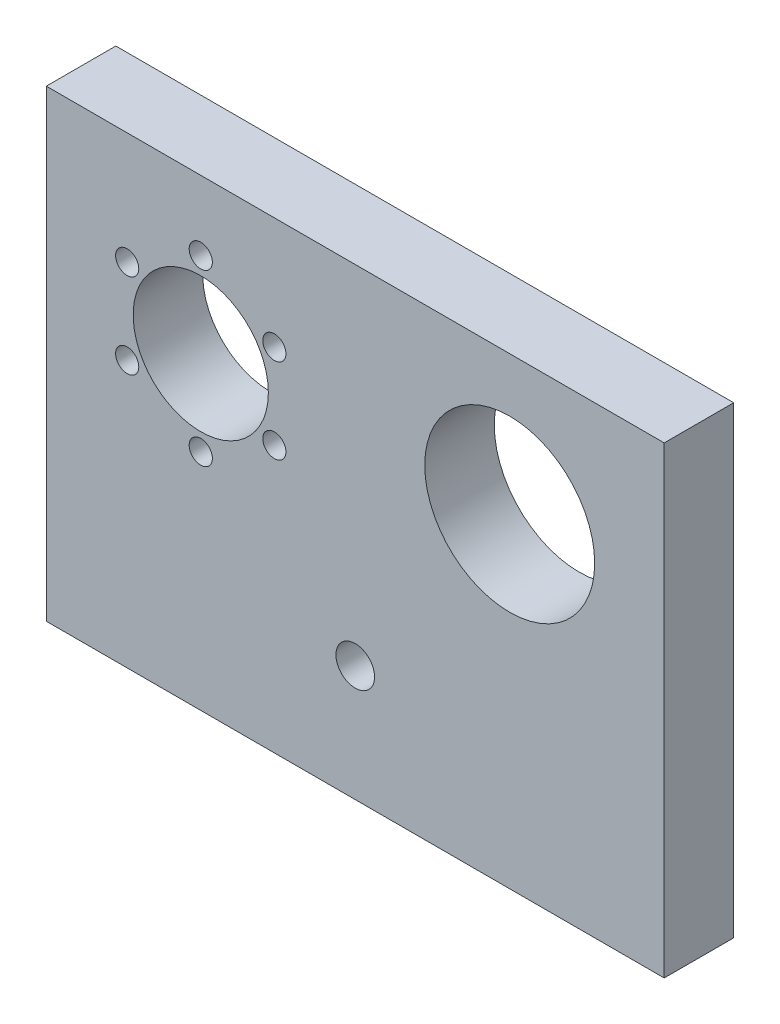
SolidWorks part; units mm, degrees
ref_plane "Front" through (0, 0, 0) normal (0, 0, 1) x (1, 0, 0)
ref_plane "Top" through (0, 0, 0) normal (0, 1, 0) x (1, 0, 0)
ref_plane "Right" through (0, 0, 0) normal (1, 0, 0) x (0, 0, -1)
sketch "Esquisse1" plane through (0, 0, 0) normal (0, 0, 1) x (1, 0, 0)
  line L1 (0, 0) -> (80, 0)
  line L2 (0, 0) -> (0, 60)
  line L3 (0, 60) -> (80, 60)
  line L4 (80, 0) -> (80, 60)
  dimension "D1" = 60
  dimension "D2" = 80
extrude "Boss.-Extru.1" add sketch "Esquisse1" along normal blind 9
sketch "Esquisse2" plane through (0, 0, 9) normal (0, 0, 1) x (1, 0, 0)
  line L0 (60, 60) -> (60, 0) construction
  line L1 (80, 60) -> (0, 60) construction
  line L2 (0, 0) -> (80, 0) construction
  line L3 (80, 0) -> (80, 60) construction
  line L4 (20, 40) -> (20, 60) construction
  line L5 (0, 60) -> (0, 0) construction
  circle A0 centre (60, 42) radius 11
  circle A1 centre (20, 40) radius 8.75
  circle A2 centre (20, 51) radius 1.5
  circle A3 centre (29.5263, 45.5) radius 1.5
  circle A4 centre (29.5263, 34.5) radius 1.5
  circle A5 centre (20, 29) radius 1.5
  circle A6 centre (10.4737, 34.5) radius 1.5
  circle A7 centre (10.4737, 45.5) radius 1.5
  point P18 (7.7118, 28.6521)
  point P19 (20, 20)
  point P29 (20, 40)
  dimension "D1" = 22
  dimension "D2" = 18
  dimension "D4" = 17.5
  dimension "D7" = 3
  dimension "D3" = 20
  dimension "D5" = 20
  dimension "D6" = 20
  dimension "D8" = 11
  dimension "D9" = 6
extrude "Enlèv. mat.-Extru.1" cut sketch "Esquisse2" against normal through all
sketch "Esquisse3" plane through (0, 0, 9) normal (0, 0, 1) x (1, 0, 0)
  circle A0 centre (40, 15) radius 2.5
  circle A1 centre (20, 40) radius 8.75 construction
  dimension "D3" = 5
  dimension "D1" = 25
  dimension "D2" = 20
extrude "Enlèv. mat.-Extru.2" cut sketch "Esquisse3" against normal through all
